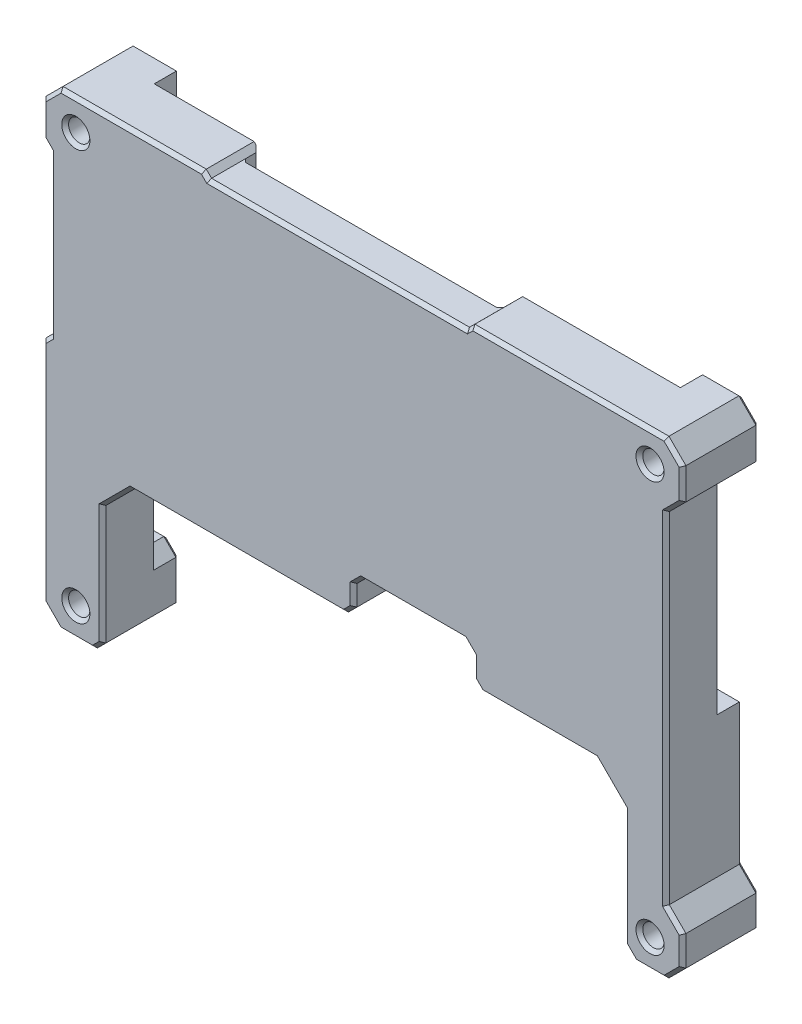
SolidWorks part; units mm, degrees
ref_plane "前视基准面" through (0, 0, 0) normal (0, 0, 1) x (1, 0, 0)
ref_plane "上视基准面" through (0, 0, 0) normal (0, 1, 0) x (1, 0, 0)
ref_plane "右视基准面" through (0, 0, 0) normal (1, 0, 0) x (0, 0, -1)
other "Configuration Table"
sketch "草图1" plane through (0, 0, 0) normal (0, 0, 1) x (1, 0, 0)
  line L1 (0, 0) -> (85, 0)
  line L2 (0, 0) -> (0, 65)
  line L3 (0, 65) -> (85, 65)
  line L4 (85, 0) -> (85, 65)
  dimension "D1" = 65
  dimension "D2" = 85
extrude "凸台-拉伸1" add sketch "草图1" along normal blind 10
sketch "草图2" plane through (0, 0, 0) normal (0, 0, -1) x (-1, 0, 0)
  circle A0 centre (-76.1669, 56.4425) radius 1.25
  circle A1 centre (-8.8888, 56.4425) radius 1.25
  circle A2 centre (-76.1669, 8.4151) radius 1.25
  circle A3 centre (-8.8888, 8.4151) radius 1.25
  dimension "D1" = 2.5
  dimension "D2" = 2.5
  dimension "D3" = 2.5
  dimension "D4" = 2.5
extrude "切除-拉伸1" cut sketch "草图2" against normal up to next
sketch "草图3" plane through (0, 0, 0) normal (0, 0, -1) x (-1, 0, 0)
  line L28 (-85, 0) -> (-85, 65) construction
  line L29 (-85, 65) -> (0, 65)
  line L30 (-85, 65) -> (-85, 0)
  line L31 (-85, 0) -> (0, 0)
  line L32 (0, 65) -> (0, 0)
  line L56 (-5, 33.4629) -> (-5.8713, 34.3342)
  line L57 (-5, 6.9926) -> (-5, 33.4629)
  line L58 (-6.9926, 5) -> (-5, 6.9926)
  line L59 (-16.2697, 5) -> (-6.9926, 5)
  line L60 (-17.4616, 6.1866) -> (-16.2697, 5)
  line L61 (-31.7436, 6.1829) -> (-17.4616, 6.1866)
  line L62 (-32.9265, 5) -> (-31.7436, 6.1829)
  line L63 (-58.7727, 5) -> (-32.9265, 5)
  line L64 (-60.0435, 6.2655) -> (-58.7727, 5)
  line L65 (-73.1524, 6.2618) -> (-60.0435, 6.2655)
  line L66 (-74.4142, 5) -> (-73.1524, 6.2618)
  line L67 (-77.9822, 5) -> (-74.4142, 5)
  line L68 (-79.9747, 6.9926) -> (-77.9822, 5)
  line L69 (-79.9747, 10.5083) -> (-79.9747, 6.9926)
  line L70 (-78.0283, 12.46) -> (-79.9747, 10.5083)
  line L71 (-78.032, 52.3531) -> (-78.0283, 12.46)
  line L72 (-79.9747, 54.2958) -> (-78.032, 52.3531)
  line L73 (-79.9747, 57.9821) -> (-79.9747, 54.2958)
  line L74 (-77.9822, 59.9747) -> (-79.9747, 57.9821)
  line L75 (-55.2451, 59.9747) -> (-77.9822, 59.9747)
  line L76 (-54.6148, 59.3497) -> (-55.2451, 59.9747)
  line L77 (-24.3949, 59.3534) -> (-54.6148, 59.3497)
  line L78 (-23.7736, 59.9747) -> (-24.3949, 59.3534)
  line L79 (-6.9926, 59.9747) -> (-23.7736, 59.9747)
  line L80 (-5, 57.9821) -> (-6.9926, 59.9747)
  line L81 (-5, 54.0174) -> (-5, 57.9821)
  line L82 (-5.875, 53.1371) -> (-5, 54.0174)
  line L83 (-5.8713, 34.3342) -> (-5.875, 53.1371)
extrude "切除-拉伸2" cut sketch "草图3" against normal up to next
sketch "草图4" plane through (0, 0, 0) normal (0, 0, -1) x (-1, 0, 0)
  line L0 (-73.1524, 6.2618) -> (-73.1524, 20.0323)
  line L1 (-73.1524, 20.0323) -> (-69.8316, 23.3532)
  line L2 (-69.8316, 23.3532) -> (-46.788, 23.3532)
  line L3 (-46.788, 23.3532) -> (-15.4038, 23.3532)
  line L4 (-15.4038, 23.3532) -> (-12.014, 19.9634)
  line L5 (-12.014, 19.9634) -> (-12.014, 6.188)
  line L6 (-31.7436, 6.1829) -> (-17.4616, 6.1866) construction
  line L7 (-12.014, 6.188) -> (-12.014, 0.194)
  line L8 (-12.014, 0.194) -> (-73.1524, 0.194)
  line L9 (-73.1524, 0.194) -> (-73.1524, 6.2618)
  line L10 (-73.1524, 6.2618) -> (-60.0435, 6.2655) construction
  dimension "D1" = 135
  dimension "D2" = 135
  dimension "D3" = 4.7938
extrude "切除-拉伸4" cut sketch "草图4" against normal up to next
sketch "草图5" plane through (0, 0, 0) normal (0, 0, -1) x (-1, 0, 0)
  line L0 (-24.3949, 59.3534) -> (-24.3949, 53.9064)
  line L1 (-24.3949, 53.9064) -> (-25.5261, 52.7749)
  line L2 (-25.5261, 52.7749) -> (-53.4826, 52.7749)
  line L3 (-53.4826, 52.7749) -> (-54.6142, 53.9061)
  line L4 (-54.6142, 53.9061) -> (-54.6148, 59.3497)
  line L5 (-24.3949, 59.3534) -> (-54.6148, 59.3497) construction
  line L6 (-23.7736, 59.9747) -> (-24.3949, 59.3534) construction
  line L7 (-24.3949, 59.3534) -> (-54.6148, 59.3497)
  dimension "D1" = 135
  dimension "D2" = 134.993
  dimension "D3" = 1.6
  dimension "D4" = 1.6
extrude "切除-拉伸7" cut sketch "草图5" against normal blind 6
sketch "草图6" plane through (0, 0, 0) normal (0, 0, -1) x (-1, 0, 0)
  line L0 (-5.8713, 34.3342) -> (-11.6713, 34.3342)
  line L1 (-5, 33.4629) -> (-5.8713, 34.3342) construction
  line L6 (-5.8713, 34.3342) -> (-5.875, 53.1371) construction
  line L7 (-5.8735, 45.2504) -> (-5.8745, 50.3342)
  line L8 (-5.8735, 45.2504) -> (-5.8713, 34.3342)
  line L9 (-5.8745, 50.3342) -> (-11.6713, 50.3342)
  line L10 (-11.6713, 50.3342) -> (-11.6713, 34.3342)
  dimension "D1" = 5.8
  dimension "D2" = 16
extrude "切除-拉伸8" cut sketch "草图6" against normal blind 6
sketch "草图7" plane through (0, 0, 0) normal (0, 0, -1) x (-1, 0, 0)
  line L0 (-76.4321, 51.2623) -> (-74.4321, 51.2623)
  line L1 (-74.4321, 51.2623) -> (-71.3195, 54.3749)
  line L2 (-71.3195, 54.3749) -> (-71.3195, 58.3749)
  line L3 (-71.3195, 58.3749) -> (-71.3195, 59.9747)
  line L4 (-76.4321, 51.2623) -> (-78.0319, 51.2623)
  line L5 (-78.0298, 28.9377) -> (-75.0298, 28.9377)
  line L6 (-75.0298, 28.9377) -> (-75.0298, 13.9377)
  line L7 (-72.9158, 11.8236) -> (-75.0298, 13.9377)
  line L8 (-24.3949, 57.6633) -> (-23.7321, 57.6633)
  line L9 (-23.7321, 57.6633) -> (-23.0617, 58.334)
  line L10 (-23.0617, 58.334) -> (-12.072, 58.334)
  line L11 (-12.072, 58.334) -> (-12.072, 55.334)
  line L12 (-12.072, 55.334) -> (-9.875, 53.1371)
  line L13 (-9.875, 53.1371) -> (-5.875, 53.1371)
  line L14 (-6.5998, 12.014) -> (-10.5998, 12.014)
  line L15 (-10.5998, 12.014) -> (-12.014, 10.5998)
  line L16 (-12.014, 10.5998) -> (-12.014, 5)
  line L17 (-6.5998, 12.014) -> (-5, 12.014)
  line L18 (-72.9158, 11.8236) -> (-73.1524, 12.0603)
  line L37 (-5.8713, 34.3342) -> (-11.6713, 34.3342)
  line L38 (-11.6713, 34.3342) -> (-11.6713, 50.3342)
  line L39 (-11.6713, 34.3342) -> (-11.6713, 50.3342)
  line L40 (-11.6713, 50.3342) -> (-5.8745, 50.3342)
  line L41 (-11.6713, 50.3342) -> (-5.8745, 50.3342)
  line L42 (-5.8745, 50.3342) -> (-5.875, 53.1371)
  line L43 (-5.875, 53.1371) -> (-5, 54.0174)
  line L44 (-5, 54.0174) -> (-5, 57.9821)
  line L45 (-5, 57.9821) -> (-6.9926, 59.9747)
  line L46 (-6.9926, 59.9747) -> (-23.7736, 59.9747)
  line L47 (-23.7736, 59.9747) -> (-24.3949, 59.3534)
  line L48 (-24.3949, 59.3534) -> (-24.3949, 53.9064)
  line L49 (-24.3949, 53.9064) -> (-25.5261, 52.7749)
  line L50 (-25.5261, 52.7749) -> (-53.4826, 52.7749)
  line L51 (-53.4826, 52.7749) -> (-54.6142, 53.9061)
  line L52 (-54.6142, 53.9061) -> (-54.6148, 59.3497)
  line L53 (-54.6148, 59.3497) -> (-55.2451, 59.9747)
  line L54 (-55.2451, 59.9747) -> (-77.9822, 59.9747)
  line L55 (-77.9822, 59.9747) -> (-79.9747, 57.9821)
  line L56 (-79.9747, 57.9821) -> (-79.9747, 54.2958)
  line L57 (-79.9747, 54.2958) -> (-78.032, 52.3531)
  line L58 (-78.032, 52.3531) -> (-78.0283, 12.46)
  line L59 (-78.0283, 12.46) -> (-79.9747, 10.5083)
  line L60 (-79.9747, 10.5083) -> (-79.9747, 6.9926)
  line L61 (-79.9747, 6.9926) -> (-77.9822, 5)
  line L62 (-77.9822, 5) -> (-74.4142, 5)
  line L63 (-74.4142, 5) -> (-73.1524, 6.2618)
  line L64 (-73.1524, 6.2618) -> (-73.1524, 20.0323)
  line L65 (-73.1524, 20.0323) -> (-69.8316, 23.3532)
  line L66 (-69.8316, 23.3532) -> (-15.4038, 23.3532)
  line L67 (-15.4038, 23.3532) -> (-12.014, 19.9634)
  line L68 (-12.014, 19.9634) -> (-12.014, 5)
  line L70 (-12.014, 5) -> (-6.9926, 5)
  line L71 (-6.9926, 5) -> (-5, 6.9926)
  line L72 (-5, 6.9926) -> (-5, 33.4629)
  line L73 (-5, 33.4629) -> (-5.8713, 34.3342)
  line L74 (-5.8713, 34.3342) -> (-11.6713, 34.3342)
  line L79 (-5.8745, 50.3342) -> (-5.875, 53.1371)
  line L80 (-5.875, 53.1371) -> (-5, 54.0174)
  line L81 (-5, 54.0174) -> (-5, 57.9821)
  line L82 (-5, 57.9821) -> (-6.9926, 59.9747)
  line L83 (-6.9926, 59.9747) -> (-23.7736, 59.9747)
  line L84 (-23.7736, 59.9747) -> (-24.3949, 59.3534)
  line L85 (-24.3949, 59.3534) -> (-24.3949, 53.9064)
  line L86 (-24.3949, 53.9064) -> (-25.5261, 52.7749)
  line L87 (-25.5261, 52.7749) -> (-53.4826, 52.7749)
  line L88 (-53.4826, 52.7749) -> (-54.6142, 53.9061)
  line L89 (-54.6142, 53.9061) -> (-54.6148, 59.3497)
  line L90 (-54.6148, 59.3497) -> (-55.2451, 59.9747)
  line L91 (-55.2451, 59.9747) -> (-77.9822, 59.9747)
  line L92 (-77.9822, 59.9747) -> (-79.9747, 57.9821)
  line L93 (-79.9747, 57.9821) -> (-79.9747, 54.2958)
  line L94 (-79.9747, 54.2958) -> (-78.032, 52.3531)
  line L95 (-78.032, 52.3531) -> (-78.0283, 12.46)
  line L96 (-78.0283, 12.46) -> (-79.9747, 10.5083)
  line L97 (-79.9747, 10.5083) -> (-79.9747, 6.9926)
  line L98 (-79.9747, 6.9926) -> (-77.9822, 5)
  line L99 (-77.9822, 5) -> (-74.4142, 5)
  line L100 (-74.4142, 5) -> (-73.1524, 6.2618)
  line L101 (-73.1524, 6.2618) -> (-73.1524, 20.0323)
  line L102 (-73.1524, 20.0323) -> (-69.8316, 23.3532)
  line L103 (-69.8316, 23.3532) -> (-15.4038, 23.3532)
  line L104 (-15.4038, 23.3532) -> (-12.014, 19.9634)
  line L105 (-12.014, 19.9634) -> (-12.014, 5)
  line L107 (-12.014, 5) -> (-6.9926, 5)
  line L108 (-6.9926, 5) -> (-5, 6.9926)
  line L109 (-5, 6.9926) -> (-5, 33.4629)
  line L110 (-5, 33.4629) -> (-5.8713, 34.3342)
  dimension "D2" = 90
  dimension "D3" = 15
  dimension "D4" = 135
  dimension "D5" = 4
  dimension "D6" = 3
  dimension "D7" = 135
  dimension "D8" = 45
  dimension "D9" = 3
  dimension "D1" = 0
extrude "切除-拉伸11" cut sketch "草图7" against normal blind 4
sketch "草图8" plane through (0, 0, 4) normal (0, 0, -1) x (-1, 0, 0)
  line L1 (-73.3481, 45.9587) -> (-65.3481, 45.9587)
  line L2 (-73.3481, 45.9587) -> (-73.3481, 40.9587)
  line L3 (-73.3481, 40.9587) -> (-65.3481, 40.9587)
  line L4 (-65.3481, 45.9587) -> (-65.3481, 40.9587)
  dimension "D1" = 5
  dimension "D2" = 8
extrude "切除-拉伸12" cut sketch "草图8" against normal blind 1
sketch "草图10" plane through (0, 0, 4) normal (0, 0, -1) x (-1, 0, 0)
  line L0 (-41.5465, 34.8898) -> (-37.5465, 34.8898)
  line L1 (-46.9465, 34.8898) -> (-41.5465, 34.8898)
  line L2 (-46.9465, 34.8898) -> (-46.9465, 28.8898)
  line L3 (-46.9465, 28.8898) -> (-41.5465, 28.8898)
  line L4 (-41.5465, 34.8898) -> (-41.5465, 28.8898)
  line L5 (-37.5465, 34.8898) -> (-32.1465, 34.8898)
  line L6 (-37.5465, 34.8898) -> (-37.5465, 28.8898)
  line L7 (-37.5465, 28.8898) -> (-32.1465, 28.8898)
  line L8 (-32.1465, 34.8898) -> (-32.1465, 28.8898)
  line L9 (-37.5465, 28.8898) -> (-41.5465, 28.8898)
  dimension "D1" = 5.4
  dimension "D2" = 6
  dimension "D3" = 5.4
  dimension "D4" = 4
extrude "凸台-拉伸2" add sketch "草图10" along normal offset from surface (2.04 mm away) 3 contours L4 L1 L2 L3 | L9 L6 L0 L4 | L8 L5 L6 L7
sketch "草图11" plane through (0, 0, 4) normal (0, 0, -1) x (-1, 0, 0)
  line L1 (-40.8318, 43.6929) -> (-36.6318, 43.6929)
  line L2 (-40.8318, 43.6929) -> (-40.8318, 38.6929)
  line L3 (-40.8318, 38.6929) -> (-36.6318, 38.6929)
  line L4 (-36.6318, 43.6929) -> (-36.6318, 38.6929)
  dimension "D1" = 4.2
  dimension "D2" = 5
extrude "凸台-拉伸3" add sketch "草图11" along normal offset from surface (1.3001 mm away) 3
sketch "草图12" plane through (0, 0, 4) normal (0, 0, -1) x (-1, 0, 0)
  line L0 (-24.6106, 30.6859) -> (-32.1465, 34.8898)
  line L1 (-30.6106, 30.6859) -> (-18.6106, 30.6859)
  line L2 (-30.6106, 30.6859) -> (-30.6106, 24.6859)
  line L3 (-30.6106, 24.6859) -> (-18.6106, 24.6859)
  line L4 (-18.6106, 30.6859) -> (-18.6106, 24.6859)
  line L5 (-32.1465, 34.8898) -> (-46.9465, 34.8898) construction
  line L6 (-32.1465, 28.8898) -> (-32.1465, 34.8898) construction
  line L7 (-32.1465, 34.8898) -> (-32.1465, 28.8898)
  line L8 (-32.1465, 28.8898) -> (-30.6106, 27.6859)
  line M47 (-32.1465, 34.8898) -> (-32.1465, 28.8898)
  dimension "D1" = 12
  dimension "D2" = 6
extrude "凸台-拉伸4" add sketch "草图12" along normal up to surface (2.04 mm away) contours L4 L1 L2 L3 | L8 L2 L1 L0 M47 up to face at (39.5465, 31.8898, 1.96)
sketch "草图13" plane through (0, 0, 4) normal (0, 0, -1) x (-1, 0, 0)
  line L1 (-62.8902, 40.6188) -> (-59.7758, 40.6188)
  line L2 (-62.8902, 40.6188) -> (-62.8902, 35.6362)
  line L3 (-62.8902, 35.6362) -> (-59.7758, 35.6362)
  line L4 (-59.7758, 40.6188) -> (-59.7758, 35.6362)
extrude "凸台-拉伸5" add sketch "草图13" along normal blind 2
sketch "草图15" plane through (0, 0, 10) normal (0, 0, 1) x (1, 0, 0)
  line L0 (69.8316, 23.3532) -> (15.4038, 23.3532) construction
  line L1 (41.4288, 23.3532) -> (55.4288, 23.3532)
  line L2 (41.4288, 23.3532) -> (41.4288, 27.7532)
  line L3 (41.4288, 27.7532) -> (55.4288, 27.7532)
  line L4 (55.4288, 23.3532) -> (55.4288, 27.7532)
  dimension "D1" = 14
  dimension "D2" = 4.4
extrude "切除-拉伸13" cut sketch "草图15" against normal up to surface (6 mm away) up to face at (69.3481, 43.4587, 4)
chamfer "倒角1" distance 1 angle 45 5 edges at (12.014, 5, 5) (55.4288, 23.3532, 7) (55.4288, 27.7532, 7) (41.4288, 27.7532, 7) (41.4288, 23.3532, 7)
chamfer "倒角2" distance 0.6 angle 45 4 edges at (59.7758, 38.1275, 4) (61.333, 40.6188, 4) (62.8902, 38.1275, 4) (61.333, 35.6362, 4)
chamfer "倒角5" distance 0.6 angle 45 4 edges at (36.6318, 41.1929, 4) (38.7318, 38.6929, 4) (40.8318, 41.1929, 4) (38.7318, 43.6929, 4)
sketch "草图16" plane through (0, 0, 4) normal (0, 0, -1) x (-1, 0, 0)
  circle A0 centre (-17.8941, 26.9463) radius 1.6
  dimension "D1" = 3.2
extrude "切除-拉伸14" [suppressed] cut sketch "草图16" against normal through all both and the other way through all
sketch "草图17" plane through (0, 0, 0) normal (0, 0, -1) x (-1, 0, 0)
  line L0 (-12.072, 58.334) -> (-12.072, 59.9747)
  line L2 (-6.9926, 59.9747) -> (-23.7736, 59.9747) construction
  line L15 (-24.3949, 59.3534) -> (-24.3949, 57.6633)
  line L16 (-24.3949, 57.6633) -> (-23.7321, 57.6633)
  line L17 (-23.7321, 57.6633) -> (-23.0617, 58.334)
  line L18 (-23.0617, 58.334) -> (-12.072, 58.334)
  line L19 (-12.072, 58.334) -> (-12.072, 55.334)
  line L20 (-12.072, 55.334) -> (-9.875, 53.1371)
  line L21 (-9.875, 53.1371) -> (-5.875, 53.1371)
  line L22 (-5.875, 53.1371) -> (-5, 54.0174)
  line L23 (-5, 54.0174) -> (-5, 57.9821)
  line L24 (-5, 57.9821) -> (-6.9926, 59.9747)
  line L25 (-6.9926, 59.9747) -> (-23.7736, 59.9747)
  line L26 (-23.7736, 59.9747) -> (-24.3949, 59.3534)
  line L27 (-24.3949, 59.3534) -> (-24.3949, 57.6633)
  line L28 (-24.3949, 57.6633) -> (-23.7321, 57.6633)
  line L29 (-23.7321, 57.6633) -> (-23.0617, 58.334)
  line L30 (-23.0617, 58.334) -> (-12.072, 58.334)
  line L31 (-12.072, 58.334) -> (-12.072, 55.334)
  line L32 (-12.072, 55.334) -> (-9.875, 53.1371)
  line L33 (-9.875, 53.1371) -> (-5.875, 53.1371)
  line L34 (-5.875, 53.1371) -> (-5, 54.0174)
  line L35 (-5, 54.0174) -> (-5, 57.9821)
  line L36 (-5, 57.9821) -> (-6.9926, 59.9747)
  line L37 (-6.9926, 59.9747) -> (-23.7736, 59.9747)
  line L38 (-23.7736, 59.9747) -> (-24.3949, 59.3534)
  line M15 (-24.3949, 59.3534) -> (-24.3949, 57.6633)
  line M16 (-24.3949, 57.6633) -> (-23.7321, 57.6633)
  line M17 (-23.7321, 57.6633) -> (-23.0617, 58.334)
  line M18 (-23.0617, 58.334) -> (-12.072, 58.334)
  line M25 (-6.9926, 59.9747) -> (-23.7736, 59.9747)
  line M26 (-23.7736, 59.9747) -> (-24.3949, 59.3534)
  dimension "D1" = 0
extrude "切除-拉伸15" cut sketch "草图17" against normal up to surface (4 mm away) contours L0 M18 M25 M26 M15 M16 M17 up to face at (38.7318, 41.1929, 4)
sketch "草图18" plane through (0, 0, 0) normal (0, 0, -1) x (-1, 0, 0)
  line L0 (-73.7195, 59.9747) -> (-73.7195, 54.0502)
  line L1 (-71.3195, 59.9747) -> (-77.9822, 59.9747) construction
  line L2 (-73.7195, 54.0502) -> (-75.4166, 52.3531)
  line L3 (-75.4166, 52.3531) -> (-78.032, 52.3531)
  line L12 (-78.032, 52.3531) -> (-78.0319, 51.2623)
  line L13 (-78.0319, 51.2623) -> (-74.4321, 51.2623)
  line L14 (-74.4321, 51.2623) -> (-71.3195, 54.3749)
  line L15 (-71.3195, 54.3749) -> (-71.3195, 59.9747)
  line L16 (-71.3195, 59.9747) -> (-77.9822, 59.9747)
  line L17 (-77.9822, 59.9747) -> (-79.9747, 57.9821)
  line L18 (-79.9747, 57.9821) -> (-79.9747, 54.2958)
  line L19 (-79.9747, 54.2958) -> (-78.032, 52.3531)
  line L20 (-78.032, 52.3531) -> (-78.0319, 51.2623)
  line L21 (-78.0319, 51.2623) -> (-74.4321, 51.2623)
  line L22 (-74.4321, 51.2623) -> (-71.3195, 54.3749)
  line L23 (-71.3195, 54.3749) -> (-71.3195, 59.9747)
  line L24 (-71.3195, 59.9747) -> (-77.9822, 59.9747)
  line L25 (-77.9822, 59.9747) -> (-79.9747, 57.9821)
  line L26 (-79.9747, 57.9821) -> (-79.9747, 54.2958)
  line L27 (-79.9747, 54.2958) -> (-78.032, 52.3531)
  line M13 (-78.032, 52.3531) -> (-78.0319, 51.2623)
  line M14 (-78.0319, 51.2623) -> (-74.4321, 51.2623)
  line M15 (-74.4321, 51.2623) -> (-71.3195, 54.3749)
  line M16 (-71.3195, 54.3749) -> (-71.3195, 59.9747)
  line M17 (-71.3195, 59.9747) -> (-77.9822, 59.9747)
  dimension "D1" = 0
  dimension "D2" = 2.4
  dimension "D3" = 2.4
extrude "切除-拉伸16" cut sketch "草图18" against normal up to surface (4 mm away) contours L2 L3 L0 M13 M14 M15 M16 M17 up to face at (38.7318, 41.1929, 4)
chamfer "倒角6" distance 0.4 angle 45 39 edges at (5.9963, 5.9963, 10) (5, 20.2277, 10) (5.4357, 33.8986, 10) (5.8732, 43.7356, 10) (5.4375, 53.5772, 10) (5, 55.9998, 10) (5.9963, 58.9784, 10) (15.3831, 59.9747, 10) (24.0842, 59.6641, 10) (39.5048, 59.3515, 10) (54.93, 59.6622, 10) (66.6136, 59.9747, 10) (78.9785, 58.9784, 10) (79.9747, 56.139, 10) (79.0034, 53.3245, 10) (78.0302, 32.4066, 10) (79.0015, 11.4841, 10) (79.9747, 8.7504, 10) (78.9785, 5.9963, 10) (76.1982, 5, 10) (73.7833, 5.6309, 10) (73.1524, 13.1471, 10) (71.492, 21.6927, 10) (27.9163, 23.3532, 10) (55.9288, 23.8532, 10) (55.4288, 25.5532, 10) (54.9288, 27.2532, 10) (48.4288, 27.7532, 10) (41.9288, 27.2532, 10) (41.4288, 25.5532, 10) (40.9288, 23.8532, 10) (13.7089, 21.6583, 10) (12.014, 12.9817, 10) (11.514, 5.5, 10) (9.0033, 5, 10) (7.6388, 56.4425, 10) (74.9169, 8.4151, 10) (7.6388, 8.4151, 10) (74.9169, 56.4425, 10)
chamfer "倒角7" distance 0.4 angle 45 8 edges at (59.7758, 38.1275, 2) (61.333, 35.6362, 2) (62.8902, 38.1275, 2) (61.333, 40.6188, 2) (40.8318, 41.1929, 2.6999) (38.7318, 43.6929, 2.6999) (36.6318, 41.1929, 2.6999) (38.7318, 38.6929, 2.6999)
chamfer "倒角8" distance 0.4 angle 45 8 edges at (8.7729, 50.3342, 6) (11.6713, 50.3342, 5) (11.6713, 42.3342, 6) (8.7713, 34.3342, 6) (11.6713, 34.3342, 5) (8.7729, 50.3342, 4) (11.6713, 42.3342, 4) (8.7713, 34.3342, 4)
chamfer "倒角9" distance 0.4 angle 45 10 edges at (54.6145, 56.6279, 4) (54.6145, 56.6279, 6) (54.0484, 53.3405, 4) (54.0484, 53.3405, 6) (24.3949, 56.6299, 4) (24.3949, 56.6299, 6) (24.9605, 53.3407, 4) (24.9605, 53.3407, 6) (39.5044, 52.7749, 4) (39.5044, 52.7749, 6)
chamfer "倒角11" distance 0.4 angle 45 4 edges at (69.3481, 45.9587, 5) (65.3481, 43.4587, 5) (69.3481, 40.9587, 5) (73.3481, 43.4587, 5)
sketch "草图19" plane through (0, 0, 4) normal (0, 0, -1) x (-1, 0, 0)
  line L1 (-67.6316, 31.7532) -> (-58.2316, 31.7532)
  line L2 (-67.6316, 31.7532) -> (-67.6316, 23.3532)
  line L3 (-67.6316, 23.3532) -> (-58.2316, 23.3532)
  line L4 (-58.2316, 31.7532) -> (-58.2316, 23.3532)
  line L5 (-69.8316, 23.3532) -> (-56.4288, 23.3532) construction
  dimension "D1" = 9.4
  dimension "D2" = 8.4
  dimension "D3" = 2.2
extrude "切除-拉伸17" cut sketch "草图19" against normal blind 2.4
chamfer "倒角12" distance 0.4 angle 45 11 edges at (67.6316, 27.5532, 6.4) (67.6316, 23.3532, 5.2) (62.9316, 31.7532, 6.4) (67.6316, 31.7532, 5.2) (58.2316, 27.5532, 6.4) (58.2316, 31.7532, 5.2) (62.9316, 23.3532, 6.4) (58.2316, 23.3532, 5.2) (67.6316, 27.5532, 4) (58.2316, 27.5532, 4) (62.9316, 31.7532, 4)
chamfer "倒角13" [suppressed] distance 0.4
chamfer "倒角14" distance 0.4 angle 45 9 edges at (46.9465, 31.8898, 1.96) (39.5465, 34.8898, 1.96) (28.3786, 32.7879, 1.96) (21.6106, 30.6859, 1.96) (18.6106, 27.6859, 1.96) (24.6106, 24.6859, 1.96) (30.6106, 26.1859, 1.96) (31.3786, 28.2879, 1.96) (39.5465, 28.8898, 1.96)
chamfer "倒角15" distance 0.4 angle 45 9 edges at (46.9465, 31.8898, 4) (39.5465, 34.8898, 4) (28.3786, 32.7879, 4) (21.6106, 30.6859, 4) (18.6106, 27.6859, 4) (24.6106, 24.6859, 4) (30.6106, 26.1859, 4) (31.3786, 28.2879, 4) (39.5465, 28.8898, 4)
sketch "草图20" plane through (0, 0, 0) normal (0, 0, -1) x (-1, 0, 0)
  line L0 (-6.9926, 59.9747) -> (-12.072, 59.9747) construction
  line L1 (-12.072, 59.9747) -> (-12.072, 55.334) construction
  line L2 (-12.072, 55.334) -> (-9.875, 53.1371) construction
  line L3 (-9.875, 53.1371) -> (-5.875, 53.1371) construction
  line L4 (-5.875, 53.1371) -> (-5, 54.0174) construction
  line L5 (-5, 54.0174) -> (-5, 57.9821) construction
  line L6 (-5, 57.9821) -> (-6.9926, 59.9747) construction
  line L7 (-73.7195, 54.0502) -> (-73.7195, 59.9747) construction
  line L8 (-73.7195, 59.9747) -> (-77.9822, 59.9747) construction
  line L9 (-77.9822, 59.9747) -> (-79.9747, 57.9821) construction
  line L10 (-79.9747, 57.9821) -> (-79.9747, 54.2958) construction
  line L11 (-79.9747, 54.2958) -> (-78.032, 52.3531) construction
  line L12 (-78.032, 52.3531) -> (-75.4166, 52.3531) construction
  line L13 (-75.4166, 52.3531) -> (-73.7195, 54.0502) construction
  line L14 (-73.1524, 6.2618) -> (-73.1524, 12.0603) construction
  line L15 (-73.1524, 12.0603) -> (-75.0298, 13.9377) construction
  line L16 (-75.0298, 13.9377) -> (-75.0298, 28.9377) construction
  line L17 (-75.0298, 28.9377) -> (-78.0298, 28.9377) construction
  line L18 (-78.0298, 28.9377) -> (-78.0283, 12.46) construction
  line L19 (-78.0283, 12.46) -> (-79.9747, 10.5083) construction
  line L20 (-79.9747, 10.5083) -> (-79.9747, 6.9926) construction
  line L21 (-79.9747, 6.9926) -> (-77.9822, 5) construction
  line L22 (-77.9822, 5) -> (-74.4142, 5) construction
  line L23 (-74.4142, 5) -> (-73.1524, 6.2618) construction
  line L24 (-12.014, 10.5998) -> (-12.014, 6) construction
  line L25 (-12.014, 6) -> (-11.014, 5) construction
  line L26 (-11.014, 5) -> (-6.9926, 5) construction
  line L27 (-6.9926, 5) -> (-5, 6.9926) construction
  line L28 (-5, 6.9926) -> (-5, 12.014) construction
  line L29 (-5, 12.014) -> (-10.5998, 12.014) construction
  line L30 (-10.5998, 12.014) -> (-12.014, 10.5998) construction
  line L31 (-6.9926, 59.9747) -> (-12.072, 59.9747)
  line L32 (-12.072, 59.9747) -> (-12.072, 55.334)
  line L33 (-12.072, 55.334) -> (-9.875, 53.1371)
  line L34 (-9.875, 53.1371) -> (-5.875, 53.1371)
  line L35 (-5.875, 53.1371) -> (-5, 54.0174)
  line L36 (-5, 54.0174) -> (-5, 57.9821)
  line L37 (-5, 57.9821) -> (-6.9926, 59.9747)
  line L38 (-73.7195, 54.0502) -> (-73.7195, 59.9747)
  line L39 (-73.7195, 59.9747) -> (-77.9822, 59.9747)
  line L40 (-77.9822, 59.9747) -> (-79.9747, 57.9821)
  line L41 (-79.9747, 57.9821) -> (-79.9747, 54.2958)
  line L42 (-79.9747, 54.2958) -> (-78.032, 52.3531)
  line L43 (-78.032, 52.3531) -> (-75.4166, 52.3531)
  line L44 (-75.4166, 52.3531) -> (-73.7195, 54.0502)
  line L45 (-73.1524, 6.2618) -> (-73.1524, 12.0603)
  line L46 (-73.1524, 12.0603) -> (-75.0298, 13.9377)
  line L47 (-75.0298, 13.9377) -> (-75.0298, 28.9377)
  line L48 (-75.0298, 28.9377) -> (-78.0298, 28.9377)
  line L49 (-78.0298, 28.9377) -> (-78.0283, 12.46)
  line L50 (-78.0283, 12.46) -> (-79.9747, 10.5083)
  line L51 (-79.9747, 10.5083) -> (-79.9747, 6.9926)
  line L52 (-79.9747, 6.9926) -> (-77.9822, 5)
  line L53 (-77.9822, 5) -> (-74.4142, 5)
  line L54 (-74.4142, 5) -> (-73.1524, 6.2618)
  line L55 (-12.014, 10.5998) -> (-12.014, 6)
  line L56 (-12.014, 6) -> (-11.014, 5)
  line L57 (-11.014, 5) -> (-6.9926, 5)
  line L58 (-6.9926, 5) -> (-5, 6.9926)
  line L59 (-5, 6.9926) -> (-5, 12.014)
  line L60 (-5, 12.014) -> (-10.5998, 12.014)
  line L61 (-10.5998, 12.014) -> (-12.014, 10.5998)
  line L62 (-6.9926, 59.9747) -> (-12.072, 59.9747)
  line L63 (-12.072, 59.9747) -> (-12.072, 55.334)
  line L64 (-12.072, 55.334) -> (-9.875, 53.1371)
  line L65 (-9.875, 53.1371) -> (-5.875, 53.1371)
  line L66 (-5.875, 53.1371) -> (-5, 54.0174)
  line L67 (-5, 54.0174) -> (-5, 57.9821)
  line L68 (-5, 57.9821) -> (-6.9926, 59.9747)
  line L69 (-12.014, 10.5998) -> (-12.014, 6)
  line L70 (-12.014, 6) -> (-11.014, 5)
  line L71 (-11.014, 5) -> (-6.9926, 5)
  line L72 (-6.9926, 5) -> (-5, 6.9926)
  line L73 (-5, 6.9926) -> (-5, 12.014)
  line L74 (-5, 12.014) -> (-10.5998, 12.014)
  line L75 (-10.5998, 12.014) -> (-12.014, 10.5998)
  line L76 (-73.1524, 6.2618) -> (-73.1524, 12.0603)
  line L77 (-73.1524, 12.0603) -> (-75.0298, 13.9377)
  line L78 (-75.0298, 13.9377) -> (-75.0298, 28.9377)
  line L79 (-75.0298, 28.9377) -> (-78.0298, 28.9377)
  line L80 (-78.0298, 28.9377) -> (-78.0283, 12.46)
  line L81 (-78.0283, 12.46) -> (-79.9747, 10.5083)
  line L82 (-79.9747, 10.5083) -> (-79.9747, 6.9926)
  line L83 (-79.9747, 6.9926) -> (-77.9822, 5)
  line L84 (-77.9822, 5) -> (-74.4142, 5)
  line L85 (-74.4142, 5) -> (-73.1524, 6.2618)
  line L86 (-73.7195, 54.0502) -> (-73.7195, 59.9747)
  line L87 (-73.7195, 59.9747) -> (-77.9822, 59.9747)
  line L88 (-77.9822, 59.9747) -> (-79.9747, 57.9821)
  line L89 (-79.9747, 57.9821) -> (-79.9747, 54.2958)
  line L90 (-79.9747, 54.2958) -> (-78.032, 52.3531)
  line L91 (-78.032, 52.3531) -> (-75.4166, 52.3531)
  line L92 (-75.4166, 52.3531) -> (-73.7195, 54.0502)
  circle A1 centre (-76.1669, 8.4151) radius 1.25
  circle A2 centre (-76.1669, 8.4151) radius 1.25
  circle A3 centre (-76.1669, 56.4425) radius 1.25
  circle A4 centre (-76.1669, 56.4425) radius 1.25
  circle A5 centre (-8.8888, 56.4425) radius 1.25
  circle A6 centre (-8.8888, 56.4425) radius 1.25
  circle A7 centre (-8.8888, 8.4151) radius 1.25
  circle A8 centre (-8.8888, 8.4151) radius 1.25
  dimension "D1" = 0
  dimension "D2" = 0
  dimension "D3" = 0
  dimension "D4" = 0
extrude "切除-拉伸18" cut sketch "草图20" against normal offset from surface (1 mm away) 9 contours L43 L44 L38 L39 L40 L41 L42 A4 | L53 L54 L45 L46 L47 L48 L49 L50 L51 L52 A2 | L36 L37 L31 L32 L33 L34 L35 A6
chamfer "倒角16" distance 0.4 angle 45 35 edges at (74.9169, 8.4151, 1) (78.9785, 5.9963, 1) (79.9747, 8.7504, 1) (79.0015, 11.4841, 1) (78.0291, 20.6989, 1) (76.5298, 28.9377, 1) (75.0298, 21.4377, 1) (74.0911, 12.999, 1) (73.1524, 9.1611, 1) (73.7833, 5.6309, 1) (76.1982, 5, 1) (7.6388, 8.4151, 1) (7.7999, 12.014, 1) (5, 9.5033, 1) (5.9963, 5.9963, 1) (9.0033, 5, 1) (11.514, 5.5, 1) (12.014, 8.2999, 1) (11.3069, 11.3069, 1) (7.6388, 56.4425, 1) (5.4375, 53.5772, 1) (7.875, 53.1371, 1) (10.9735, 54.2355, 1) (12.072, 57.6543, 1) (9.5323, 59.9747, 1) (5.9963, 58.9784, 1) (5, 55.9998, 1) (74.9169, 56.4425, 1) (79.0034, 53.3245, 1) (79.9747, 56.139, 1) (78.9785, 58.9784, 1) (75.8509, 59.9747, 1) (73.7195, 57.0124, 1) (74.568, 53.2016, 1) (76.7243, 52.3531, 1)
